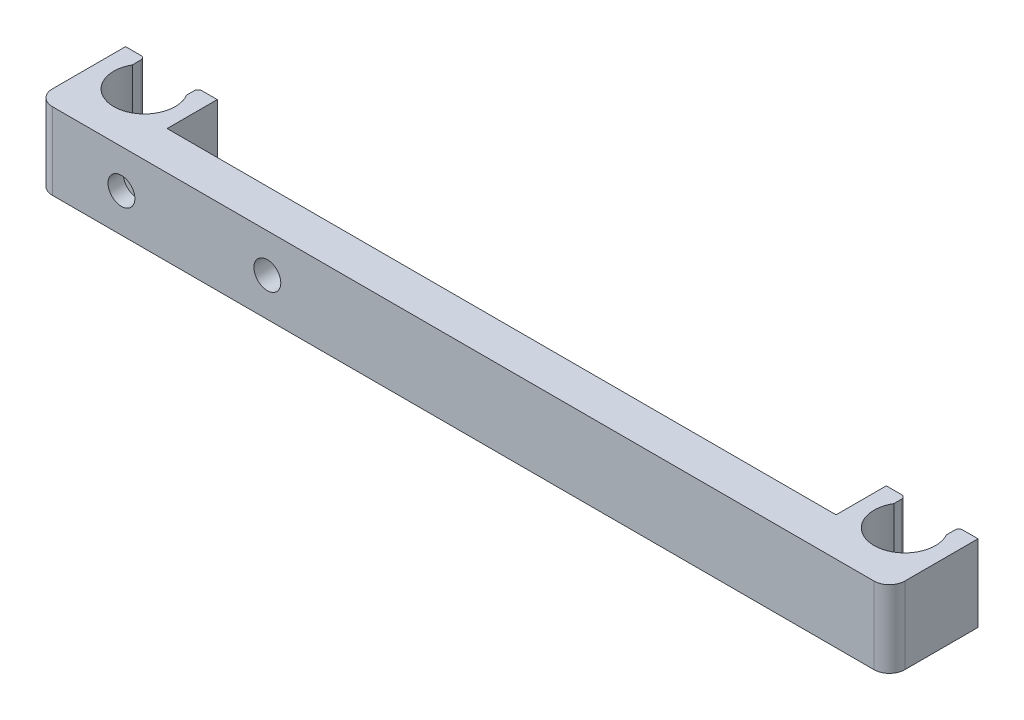
SolidWorks part; units mm, degrees
ref_plane "Front Plane" through (0, 0, 0) normal (0, 0, 1) x (1, 0, 0)
ref_plane "Top Plane" through (0, 0, 0) normal (0, 1, 0) x (1, 0, 0)
ref_plane "Right Plane" through (0, 0, 0) normal (1, 0, 0) x (0, 0, -1)
sketch "Clip" plane through (0, 0, 0) normal (0, 1, 0) x (1, 0, 0)
  line L0 (-55.5, 0) -> (55.5, 0)
  line L1 (55.5, 0) -> (55.5, 11.5365)
  line L2 (55.5, 11.5365) -> (53, 11.5365)
  line L3 (53, 11.5365) -> (53, 9.9365)
  line L4 (0, 0) -> (0, 5)
  line L5 (46.0572, 11.5365) -> (43.5572, 11.5365)
  line L6 (46.0572, 11.5365) -> (46.0572, 10.0365)
  line L7 (43.5572, 11.5365) -> (43.5572, 5)
  line L8 (43.5572, 5) -> (-43.5572, 5)
  line L9 (-43.5572, 11.5365) -> (-43.5572, 5)
  line L10 (-46.0572, 11.5365) -> (-46.0572, 10.0365)
  line L11 (-46.0572, 11.5365) -> (-43.5572, 11.5365)
  line L12 (-53, 11.5365) -> (-53, 9.9365)
  line L13 (-55.5, 11.5365) -> (-53, 11.5365)
  line L14 (-55.5, 0) -> (-55.5, 11.5365)
  arc A0 (46.0572, 10.0365) -> (53, 9.9365) centre (49.5, 8) ccw
  arc A1 (-46.0572, 10.0365) -> (-53, 9.9365) centre (-49.5, 8) cw
  dimension "D2" = 8
  dimension "D3" = 2
  dimension "D1" = 1.6
  dimension "D4" = 4
  dimension "D5" = 2.5
  dimension "D6" = 99
  dimension "D7" = 2.5
  dimension "D8" = 5
  dimension "D9" = 1.5
extrude "Boss-Extrude1" add sketch "Clip" along normal blind 10 contours L8 L9 L11 L10 A1 L12 L13 L14 L0 L1 L2 L3 A0 L6 L5 L7
fillet "Fillet1" radius 2 1 edges at (55.5, 5, 0)
fillet "Fillet2" radius 2 1 edges at (-55.5, 5, 0)
fillet "Fillet3" radius 0.5 1 edges at (46.0572, 5, -11.5365)
fillet "Fillet4" radius 0.5 1 edges at (53, 5, -11.5365)
fillet "Fillet5" radius 0.5 1 edges at (-53, 5, -11.5365)
fillet "Fillet6" radius 0.5 1 edges at (-46.0572, 5, -11.5365)
sketch "Mounting Cone" plane through (0, 0, 0) normal (0, 0, 1) x (1, 0, 0)
  line L0 (-53.5, 10) -> (53.5, 10) construction
  line L1 (-44.5, 10) -> (-44.5, 0) construction
  line L2 (-53.5, 0) -> (53.5, 0) construction
  line L3 (-53.5, 10) -> (-53.5, 0) construction
  circle A0 centre (-44.5, 5) radius 1.75
  dimension "D1" = 3.5
  dimension "D2" = 9
sketch "Mounting Hole" plane through (0, 0, 0) normal (0, 0, 1) x (1, 0, 0)
  circle A0 centre (-25.5, 5) radius 1.75
  dimension "D1" = 3.5
  dimension "D2" = 19
extrude "Cut-Extrude1" cut sketch "Mounting Hole" against normal blind 5
extrude "Cut-Extrude2" cut sketch "Mounting Cone" against normal blind 2
